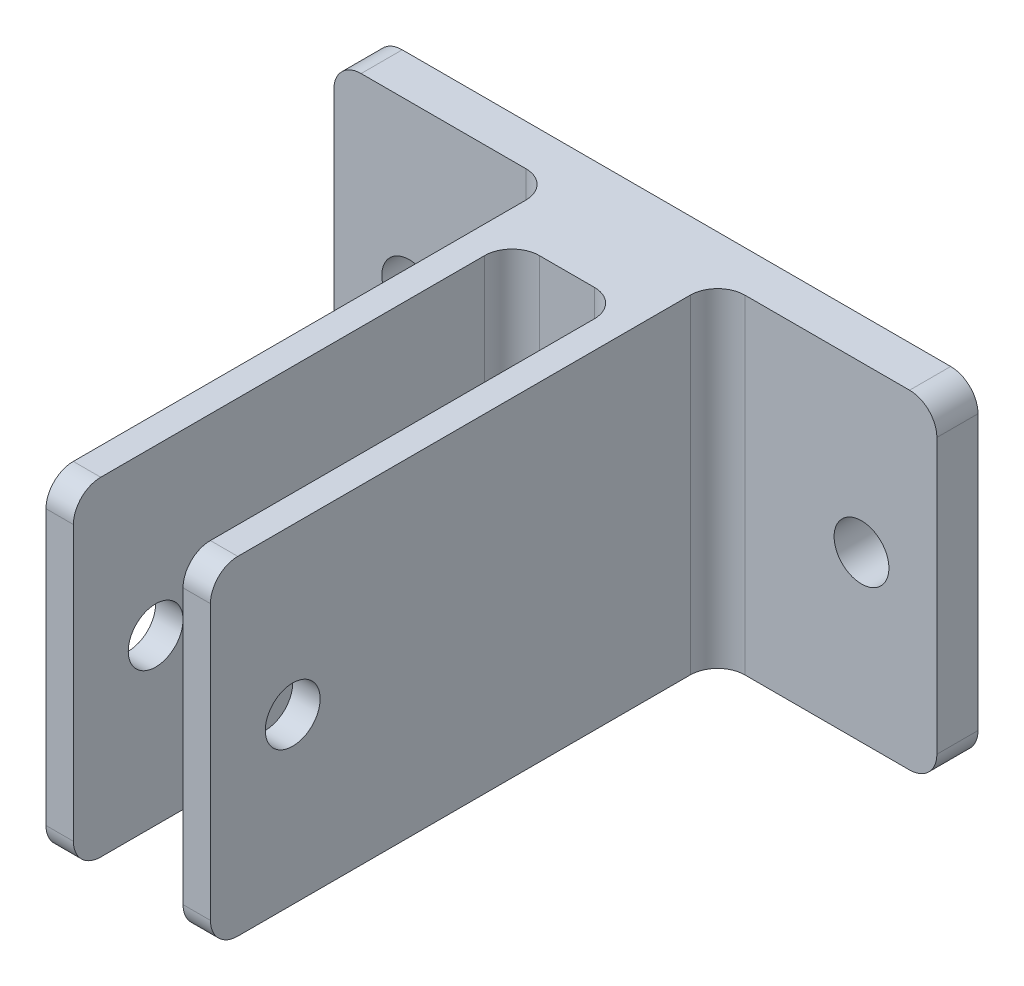
SolidWorks part; units mm, degrees
ref_plane "Front" through (0, 0, 0) normal (0, 0, 1) x (1, 0, 0)
ref_plane "Top" through (0, 0, 0) normal (0, 1, 0) x (1, 0, 0)
ref_plane "Right" through (0, 0, 0) normal (1, 0, 0) x (0, 0, -1)
sketch "Sketch1" plane through (0, 0, 0) normal (0, 1, 0) x (1, 0, 0)
  line L0 (-34.925, 0) -> (34.925, 0)
  line L1 (34.925, 0) -> (34.925, -4.7625)
  line L2 (34.925, -4.7625) -> (9.525, -4.7625)
  line L3 (9.525, -4.7625) -> (9.525, -63.5)
  line L4 (9.525, -63.5) -> (6.35, -63.5)
  line L5 (6.35, -63.5) -> (6.35, -12.7)
  line L6 (6.35, -12.7) -> (-6.35, -12.7)
  line L7 (-6.35, -12.7) -> (-6.35, -63.5)
  line L8 (-6.35, -63.5) -> (-9.525, -63.5)
  line L9 (-9.525, -63.5) -> (-9.525, -4.7625)
  line L10 (-9.525, -4.7625) -> (-34.925, -4.7625)
  line L11 (-34.925, -4.7625) -> (-34.925, 0)
  line L12 (0, -12.7) -> (0, 0) construction
  dimension "Wall Thickness 3" = 12.7
  dimension "Wall Thickness 2" = 4.7625
  dimension "C" = 69.85
  dimension "Max Panel Thickness" = 12.7
  dimension "A" = 63.5
  dimension "Wall Thickness 1" = 3.175
extrude "Extrude1" add sketch "Sketch1" along normal mid plane 38.1
sketch "Sketch2" plane through (0, 0, 0) normal (0, 0, 1) x (1, 0, 0)
  line L0 (-26.1937, 0) -> (26.1937, 0) construction
  circle A0 centre (-26.1937, 0) radius 3.175
  circle A1 centre (26.1937, 0) radius 3.175
extrude "Extrude2" cut sketch "Sketch2" along normal through all
sketch "Sketch3" plane through (0, 0, -0.6698) normal (1, 0, 0) x (0, 0, -1)
  line L1 (-64.1698, 19.05) -> (-64.1698, -19.05) construction
  circle A0 centre (-54.6448, 0) radius 3.175
  dimension "D1" = 6.35
extrude "Extrude3" cut sketch "Sketch3" along normal through all and the other way through all
fillet "Fillet3" radius 3.1623 12 edges at (9.525, 0, 4.7625) (7.9375, -19.05, 63.5) (7.9375, 19.05, 63.5) (6.35, 0, 12.7) (-6.35, 0, 12.7) (-7.9375, -19.05, 63.5) (-7.9375, 19.05, 63.5) (34.925, -19.05, 2.3813) (34.925, 19.05, 2.3813) (-34.925, -19.05, 2.3813) (-34.925, 19.05, 2.3813) (-9.525, 0, 4.7625)
sketch "Sketch5" [suppressed] plane through (0, 0, 0) normal (0, 0, 1) x (1, 0, 0)
  circle A0 centre (0, 0) radius 3.175
  circle A1 centre (38.1, 0) radius 3.175 construction
extrude "Cut-Extrude1" [suppressed] cut sketch "Sketch5" along normal through all
chamfer "Chamfer1" [suppressed] distance 3.175 angle 45
sketch "Sketch4" plane through (0, 0, 0) normal (0, 1, 0) x (1, 0, 0)
  line L0 (9.525, -50.8) -> (6.35, -50.8) construction
  line L1 (6.35, -57.15) -> (9.525, -57.15) construction
  line L2 (-6.35, -50.8) -> (-9.525, -50.8) construction
  line L3 (-9.525, -57.15) -> (-6.35, -57.15) construction
  line L4 (9.525, -50.8) -> (6.35, -50.8)
  line L5 (6.35, -57.15) -> (9.525, -57.15)
  line L6 (-6.35, -50.8) -> (-9.525, -50.8)
  line L7 (-9.525, -57.15) -> (-6.35, -57.15)
  line L8 (-10.541, -53.975) -> (-5.334, -53.975) construction
  line L9 (-6.35, -53.975) -> (-9.525, -53.975) construction
  line L10 (5.334, -53.975) -> (10.541, -53.975) construction
  point P14 (-7.9375, -53.975)
  point P15 (-7.9375, -50.8)
  point P16 (7.9375, -53.975)
  point P17 (7.9375, -50.8)
  dimension "D1" = 1.016
equation "\"D1@Sketch3\" = \"Hole Dia@Sketch2\""
equation "\"D1@Fillet3\" = \"B@Extrude1\" * .083"
equation "\"D1@Chamfer1\" = \"Hole Dia@Sketch2\" * .5"
